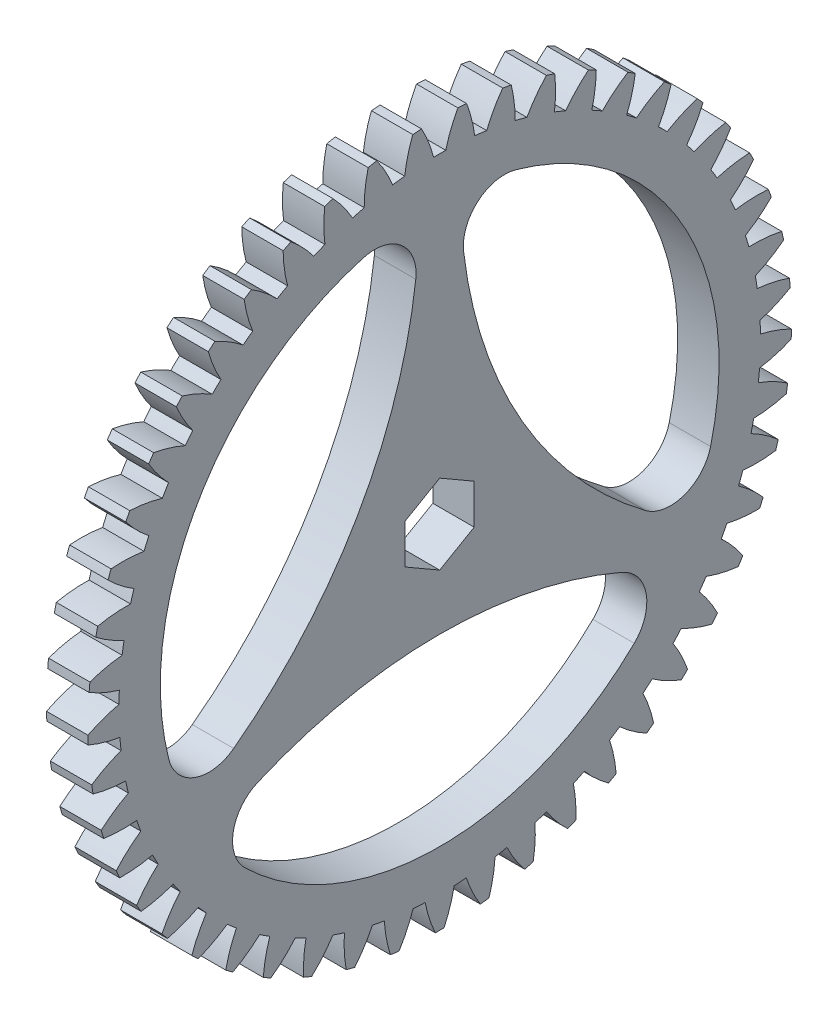
SolidWorks part; units mm, degrees
material "Plain Carbon Steel"
ref_plane "Plane1" through (0, 0, 0) normal (0, 0, 1) x (1, 0, 0)
ref_plane "Plane2" through (0, 0, 0) normal (0, 1, 0) x (1, 0, 0)
ref_plane "Plane3" through (0, 0, 0) normal (1, 0, 0) x (0, 0, -1)
sketch "HoldingSke" plane through (0, 0, 0) normal (0, 1, 0) x (1, 0, 0)
  line L0 (0, 0) -> (0.6561, -0.7547)
  line L1 (-15, 0) -> (100, 0) construction
  line L2 (0, 0) -> (-2.1039, 2.3779)
  line L3 (0, 0) -> (-11.863, 4.5341)
  line L4 (0, 0) -> (5.6657, 6.5177)
  line L5 (0, 0) -> (-46.8476, -17.4728)
  line L6 (0, 0) -> (-2.4869, -1.6779)
  line L7 (-2.1039, 2.3779) -> (8.6586, 51.2059)
  line L8 (-76.2, 54.61) -> (-75.7, 54.61)
  line L9 (-71.009, 38.7566) -> (-53.1078, 45.2721)
  line L10 (-76.2, 71.12) -> (104.1128, 71.12)
  line L11 (0, 0) -> (-3, 0)
  line L12 (-76.2, 101.6) -> (-76.162, 101.6)
  line L13 (24.9733, 27.94) -> (52.9518, 28.4284)
  line L14 (24.9733, 27.94) -> (24.9743, 27.94)
  line L15 (24.9733, 27.94) -> (100.4006, 29.5858)
  line L16 (-63.627, -1) -> (-12.827, -1)
  circle A0 centre (0, 0) radius 1.5
  circle A1 centre (0, 0) radius 23.249
  circle A2 centre (0, 0) radius 37.5
  circle A3 centre (0, 0) radius 1.5
  dimension "MHD" = 46.498
  dimension "Hub_dia" = 75
  dimension "Bore" = 3
  dimension "MBD" = 3
  dimension "Num_teeth" = 49
  dimension "Pitch_radius" = 180.3128
  dimension "Pitch" = 1
  dimension "Width" = 3
  dimension "Overall_len" = 50
  dimension "Show_teeth" = 49
  dimension "Thickness" = 3
  dimension "OAL" = 50.0001
  dimension "T_dim" = 0.5
  dimension "Ap" = 20
  dimension "H" = 19.05
  dimension "Backlash" = 0.038
  dimension "Addendum_fac" = 1
  dimension "Dedendum_fac" = 1.25
  dimension "Clearance_fac" = 0.25
  dimension "Dedendum_add" = 0.001
  dimension "Module" = 1
sketch "BasProSke" plane through (0, 0, 0) normal (0, 1, 0) x (1, 0, 0)
  line L0 (-10, 0) -> (60, 0) construction
  line L1 (0, 0) -> (0, 25.5)
  line L2 (0, 0) -> (3, 0)
  line L3 (3, 0) -> (3, 25.5)
  line L4 (3, 25.5) -> (0, 25.5)
  dimension "Diameter" = 51
  dimension "Thickness" = 3
revolve "Base-Revolve" add sketch "BasProSke" angle 360 about L0
sketch "TooCutSke" plane through (0, 0, 0) normal (1, 0, 0) x (0, 0, -1)
  line L1 (0, 0) -> (0, 107) construction
  line L2 (0, 0) -> (-0.8518, 24.4852) construction
  line L3 (0, 0) -> (-3.1381, 48.8783) construction
  line L4 (-0.8518, 24.4852) -> (-1.569, 24.4391) construction
  arc A0 (0.4386, 23.2449) -> (-0.4386, 23.2449) centre (0, 0) ccw
  arc A1 (1.3315, 25.4906) -> (-1.3315, 25.4906) centre (0, 0) ccw
  circle A2 centre (0, 0) radius 24.5 construction
  circle A3 centre (0, 0) radius 23.0225 construction
  arc A4 (-0.4386, 23.2449) -> (-1.3315, 25.4906) centre (-9.9221, 20.7746) ccw
  arc A5 (1.3315, 25.4906) -> (0.4386, 23.2449) centre (9.9221, 20.7746) ccw
  dimension "Root_dia" = 46.498
  dimension "Overcut_dia" = 51.0508
  dimension "Pitch_dia" = 49
  dimension "Base_dia" = 46.0449
  dimension "Flank_rad" = 9.8
  dimension "Half_ang" = 3.673
  dimension "Half_CT" = 0.7188
extrude "ToothCut" cut sketch "TooCutSke" along normal through all
fillet "Breaks" [suppressed] radius 0.02
fillet "RootFillets" [suppressed] radius 0.251
pattern_circular "TeethCuts" count 49 every 7.347 about axis through (-10, 0, 0) along (1, 0, 0) of "ToothCut", "RootFillets", "Breaks"
sketch "HubNeaOneSke" plane through (0, 0, 0) normal (-1, 0, 0) x (0, 0, 1)
  circle A0 centre (0, 0) radius 23.249
  dimension "Diameter" = 46.498
extrude "HubNearOne" [suppressed] add sketch "HubNeaOneSke" along normal blind 47.0001
sketch "HubNeaBotSke" plane through (0, 0, 0) normal (-1, 0, 0) x (0, 0, 1)
  circle A0 centre (0, 0) radius 23.249
  dimension "Diameter" = 46.498
extrude "HubNearBoth" [suppressed] add sketch "HubNeaBotSke" along normal blind 23.5
ref_plane "FarPln" through (3, 0, 0) normal (1, 0, 0) x (0, 0, -1)
sketch "HubFarSke" plane through (3, 0, 0) normal (1, 0, 0) x (0, 0, -1)
  circle A0 centre (0, 0) radius 23.249
  dimension "Diameter" = 46.498
extrude "HubFar" [suppressed] add sketch "HubFarSke" along normal blind 23.5
sketch "BorSke" plane through (0, 0, 0) normal (1, 0, 0) x (0, 0, -1)
  line L1 (-2.8868, 0) -> (-1.4434, -2.5) construction
  line L2 (-1.4434, -2.5) -> (1.4434, -2.5) construction
  line L3 (1.4434, -2.5) -> (2.8868, 0) construction
  line L4 (2.8868, 0) -> (1.4434, 2.5) construction
  line L5 (1.4434, 2.5) -> (-1.4434, 2.5) construction
  line L6 (-1.4434, 2.5) -> (-2.8868, 0) construction
  circle A0 centre (0, 0) radius 1.5
  circle A1 centre (0, 0) radius 2.5 construction
  dimension "D1" = 5
  dimension "Diameter" = 3
extrude "Bore" cut sketch "BorSke" along normal mid plane 100.0001
sketch "KeySke" plane through (0, 0, 0) normal (1, 0, 0) x (0, 0, -1)
  line L0 (-0.6, 0) -> (-0.6, 2)
  line L1 (-0.6, 2) -> (0.6, 2)
  line L2 (0.6, 2) -> (0.6, 0)
  line L3 (0, 0) -> (0, 34) construction
  line L4 (-0.6, 0) -> (0.6, 0)
  dimension "Offset" = 2
  dimension "Width" = 1.2
extrude "Keyway" [suppressed] cut sketch "KeySke" along normal mid plane 100.0001
pattern_circular "Keyway2" [suppressed] count 2 every 90 about axis through (-10, 0, 0) along (1, 0, 0)
sketch "Sketch1" plane through (0, 0, 0) normal (-1, 0, 0) x (0, 0, 1)
  line L0 (0, 0) -> (0, 23.249) construction
  line L1 (0, 0) -> (20.1342, -11.6245) construction
  line L2 (0, 0) -> (-20.1342, -11.6245) construction
  line L3 (-0.75, -1.299) -> (19.3842, -12.9235) construction
  line L4 (-0.75, 1.299) -> (-20.8842, -10.3255) construction
  line L5 (1.5, 0) -> (1.5, 23.249) construction
  line L6 (0.75, 1.299) -> (20.8842, -10.3255) construction
  line L7 (0.75, -1.299) -> (-19.3842, -12.9235) construction
  line L8 (-1.5, 0) -> (-1.5, 23.249) construction
  line L10 (0, 2.8868) -> (-2.5, 1.4434)
  line L11 (-2.5, 1.4434) -> (-2.5, -1.4434)
  line L12 (-2.5, -1.4434) -> (0, -2.8868)
  line L13 (0, -2.8868) -> (2.5, -1.4434)
  line L14 (2.5, -1.4434) -> (2.5, 1.4434)
  line L15 (2.5, 1.4434) -> (0, 2.8868)
  arc A0 (0.4386, 23.2449) -> (-0.4386, 23.2449) centre (0, 0) ccw construction
  circle A1 centre (0, 0) radius 23.249 construction
  circle A2 centre (0, 0) radius 20.249
  arc A3 (1.5, 20.1934) -> (18.238, -8.7976) centre (34.9759, 20.1934) ccw
  arc A4 (-1.5, 20.1934) -> (-18.238, -8.7976) centre (-34.9759, 20.1934) cw
  arc A5 (16.738, -11.3957) -> (-16.738, -11.3957) centre (0, -40.3867) ccw
  circle A6 centre (0, 0) radius 2.5 construction
  dimension "D3" = 1.5
  dimension "D1" = 3
  dimension "D2" = 1.5
  dimension "D5" = 5
  dimension "D4" = 3
extrude "Cut-Extrude1" cut sketch "Sketch1" against normal blind 10 contours A2 A3 | A4 A2 | A2 A5 | L11 L12 L13 L14 L15 L10
ref_plane "Plane4" through (1.5, 0, 0) normal (-1, 0, 0) x (0, 0, 1)
fillet "Fillet1" radius 3 6 edges at (1.5, 20.1934, 1.5) (1.5, -8.7976, 18.238) (1.5, -11.3957, 16.738) (1.5, -11.3957, -16.738) (1.5, -8.7976, -18.238) (1.5, 20.1934, -1.5)
equation "' \"Module@HoldingSke\" = 6.35"
equation "' \"Num_teeth@HoldingSke\" = 12"
equation "' \"Ap@HoldingSke\" =  20"
equation "' \"Width@HoldingSke\" = 0.5 * 25.4"
equation "' \"Hub_dia@HoldingSke\"= 1 * 25.4"
equation "' \"Overall_len@HoldingSke\" = 1.0 * 25.4"
equation "' \"Bore@HoldingSke\" = 0.75 * 25.4"
equation "' \"T_dim@HoldingSke\" = 0.1 * 25.4"
equation "' \"Width@KeySke\" = 0.25 * 25.4"
equation "' \"Show_teeth@HoldingSke\" = 13"
equation "' \"Backlash@HoldingSke\" = 0.009 * 25.4"
equation "' \"Addendum_fac@HoldingSke\" = 1.0"
equation "' \"Dedendum_fac@HoldingSke\" = 1.25"
equation "' \"Dedendum_add@HoldingSke\" = 0.00005 * 25.4"
equation "' \"Clearance_fac@HoldingSke\" = 0.25"
equation "\"Pitch@HoldingSke\" = 1 / \"Module@HoldingSke\""
equation "\"Overcut_dia@TooCutSke\" = (\"Num_teeth@HoldingSke\" + 2 * \"Addendum_fac@HoldingSke\") / \"Pitch@HoldingSke\" + 0.002 * 25.4"
equation "\"Pitch_dia@TooCutSke\" = \"Num_teeth@HoldingSke\" / \"Pitch@HoldingSke\""
equation "\"Base_dia@TooCutSke\" = \"Num_teeth@HoldingSke\" / \"Pitch@HoldingSke\" * cos((\"Ap@HoldingSke\"  * 3.14159265 / 180))"
equation "\"Root_dia@TooCutSke\" = (\"Num_teeth@HoldingSke\" + 2) / \"Pitch@HoldingSke\" - 2 * (\"Addendum_fac@HoldingSke\" + \"Dedendum_fac@HoldingSke\") / \"Pitch@HoldingSke\" - \"Dedendum_add@HoldingSke\" * 2"
equation "\"Half_ang@TooCutSke\" = 180 / \"Num_teeth@HoldingSke\""
equation "\"Half_CT@TooCutSke\" = \"Num_teeth@HoldingSke\" / \"Pitch@HoldingSke\" * sin((3.14159265 / 2 / \"Num_teeth@HoldingSke\")) / 2 - 7 * \"Backlash@HoldingSke\" / 4"
equation "\"Flank_rad@TooCutSke\" = \"Num_teeth@HoldingSke\" / \"Pitch@HoldingSke\" / 5"
equation "\"Radius@RootFillets\" = \"Clearance_fac@HoldingSke\" / \"Pitch@HoldingSke\" + \"Dedendum_add@HoldingSke\""
equation "\"Break_rad@Breaks\" = 0.02 / \"Pitch@HoldingSke\""
equation "\"Thickness@HoldingSke\" = \"Width@HoldingSke\""
equation "\"OAL@HoldingSke\" = \"Thickness@HoldingSke\""
equation "\"MHD@HoldingSke\" = (\"Num_teeth@HoldingSke\" + 2) / \"Pitch@HoldingSke\" - 2 * (\"Addendum_fac@HoldingSke\" + \"Dedendum_fac@HoldingSke\")  / \"Pitch@HoldingSke\" - \"Dedendum_add@HoldingSke\" * 2"
equation "\"MBD@HoldingSke\" = (\"Num_teeth@HoldingSke\" + 2) / \"Pitch@HoldingSke\" - 2 * (\"Addendum_fac@HoldingSke\" + \"Dedendum_fac@HoldingSke\")  / \"Pitch@HoldingSke\" - \"Dedendum_add@HoldingSke\" * 2 - 0.002 * 25.4"
equation "\"MHD@HoldingSke\" = ((sgn( \"MHD@HoldingSke\" - \"Hub_dia@HoldingSke\" )-1)*( \"MHD@HoldingSke\" - \"Hub_dia@HoldingSke\" ))/-2+ \"Hub_dia@HoldingSke\""
equation "\"MBD@HoldingSke\" = ((sgn( \"MBD@HoldingSke\" - \"Bore@HoldingSke\" )-1)*( \"MBD@HoldingSke\" - \"Bore@HoldingSke\" ))/-2+ \"Bore@HoldingSke\""
equation "\"OAL@HoldingSke\" = ((sgn( \"OAL@HoldingSke\" - \"Overall_len@HoldingSke\" )+1)*( \"OAL@HoldingSke\" - \"Overall_len@HoldingSke\" ))/2 + \"Overall_len@HoldingSke\" + 0.000002 * 25.4"
equation "\"Num_teeth@TeethCuts\" = int( \"Show_teeth@HoldingSke\" ) + 1"
equation "\"Num_teeth@TeethCuts\" = ((sgn( \"Num_teeth@TeethCuts\" - \"Num_teeth@HoldingSke\" )-1)*( \"Num_teeth@TeethCuts\" - \"Num_teeth@HoldingSke\" ))/-2+ \"Num_teeth@HoldingSke\""
equation "\"Num_teeth@TeethCuts\" = ((sgn( \"Num_teeth@TeethCuts\" - 2.0)+1)*( \"Num_teeth@TeethCuts\" - 2.0))/2 +2.0"
equation "\"Angle@TeethCuts\" = 360.0 / \"Num_teeth@HoldingSke\""
equation "\"Diameter@BasProSke\" = (\"Num_teeth@HoldingSke\" + 2 * \"Addendum_fac@HoldingSke\") / \"Pitch@HoldingSke\""
equation "\"Thickness@BasProSke\"  = \"Thickness@HoldingSke\""
equation "' \"Fillet_rad@BasProSke\" =  \"Thickness@HoldingSke\" * 0.05"
equation "\"MHD@HoldingSke\" = ((sgn( \"MHD@HoldingSke\" - \"Root_dia@TooCutSke\" )-1)*( \"MHD@HoldingSke\" - \"Root_dia@TooCutSke\" ))/-2+ \"Root_dia@TooCutSke\""
equation "\"Diameter@HubNeaOneSke\" = \"MHD@HoldingSke\""
equation "\"Length@HubNearOne\" = \"OAL@HoldingSke\" - \"Thickness@BasProSke\""
equation "\"Diameter@HubNeaBotSke\" = \"MHD@HoldingSke\""
equation "\"Length@HubNearBoth\" = ( \"OAL@HoldingSke\" - \"Thickness@BasProSke\" ) / 2.0"
equation "\"Thickness@FarPln\" = \"Thickness@BasProSke\""
equation "\"Diameter@HubFarSke\" = \"MHD@HoldingSke\""
equation "\"Length@HubFar\" = ( \"OAL@HoldingSke\" - \"Thickness@BasProSke\" ) / 2.0"
equation "\"Diameter@BorSke\" = \"MBD@HoldingSke\""
equation "\"D1@Bore\" = \"OAL@HoldingSke\" * 2.0"
equation "\"D1@Keyway\" = \"OAL@HoldingSke\" * 2.0"
equation "\"Offset@KeySke\" = \"T_dim@HoldingSke\" + \"MBD@HoldingSke\" / 2.0"
